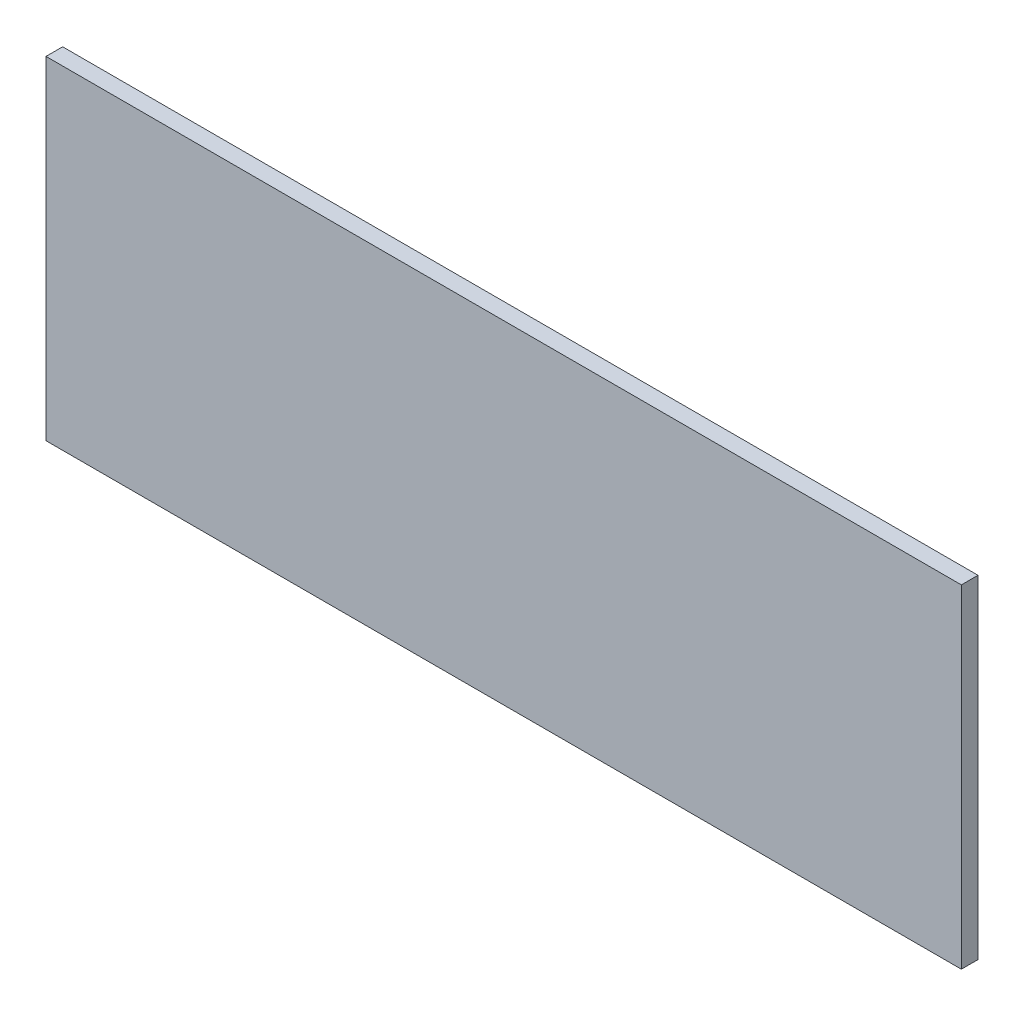
SolidWorks part; units mm, degrees
ref_plane "Plan de face" through (0, 0, 0) normal (0, 0, 1) x (1, 0, 0)
ref_plane "Plan de dessus" through (0, 0, 0) normal (0, 1, 0) x (1, 0, 0)
ref_plane "Plan de droite" through (0, 0, 0) normal (1, 0, 0) x (0, 0, -1)
sketch "Esquisse1" plane through (0, 0, 0) normal (0, 0, 1) x (1, 0, 0)
  line L1 (165, -60) -> (-165, -60)
  line L2 (165, -60) -> (165, 60)
  line L3 (165, 60) -> (-165, 60)
  line L4 (-165, -60) -> (-165, 60)
  line L5 (165, -60) -> (-165, 60) construction
  line L6 (165, 60) -> (-165, -60) construction
  point P0 (0, 0)
  dimension "D1" = 120
  dimension "D2" = 330
extrude "Boss.-Extru.1" add sketch "Esquisse1" along normal blind 6
